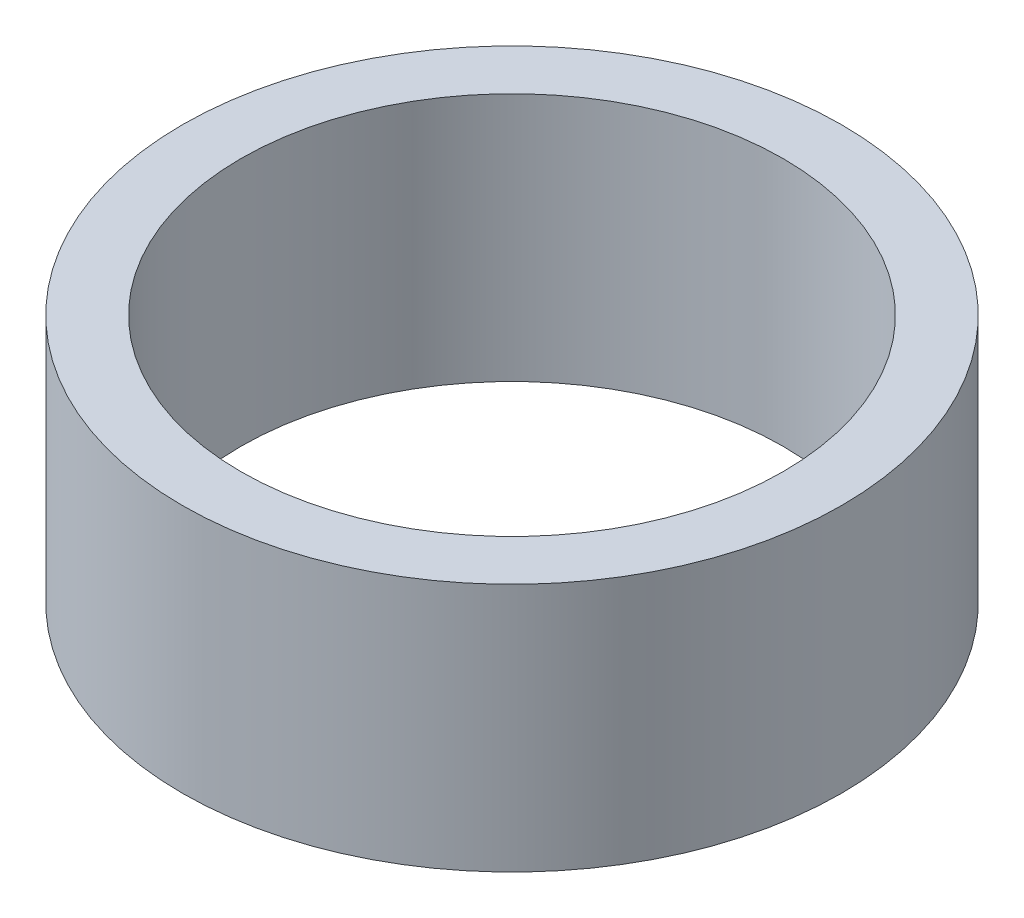
SolidWorks part; units mm, degrees
ref_plane "Front Plane" through (0, 0, 0) normal (0, 0, 1) x (1, 0, 0)
ref_plane "Top Plane" through (0, 0, 0) normal (0, 1, 0) x (1, 0, 0)
ref_plane "Right Plane" through (0, 0, 0) normal (1, 0, 0) x (0, 0, -1)
sketch "Sketch1" plane through (0, 0, 0) normal (0, 1, 0) x (1, 0, 0)
  circle A0 centre (0, 0) radius 3.2639
  circle A1 centre (0, 0) radius 3.9688
  dimension "D1" = 6.5278
  dimension "D2" = 7.9375
extrude "Boss-Extrude1" add sketch "Sketch1" along normal blind 3
